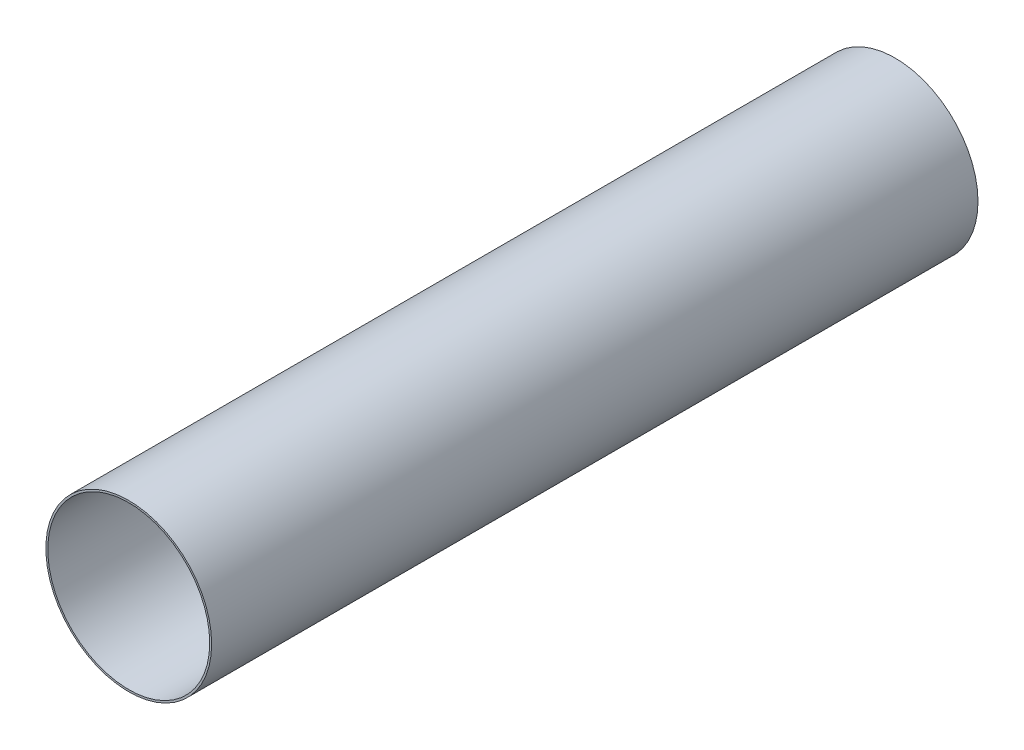
SolidWorks part; units mm, degrees
material "Hexcel AS4C (3000 Filaments)"
ref_plane "Front Plane" through (0, 0, 0) normal (0, 0, 1) x (1, 0, 0)
ref_plane "Top Plane" through (0, 0, 0) normal (0, 1, 0) x (1, 0, 0)
ref_plane "Right Plane" through (0, 0, 0) normal (1, 0, 0) x (0, 0, -1)
sketch "Sketch1" plane through (0, 0, 0) normal (0, 0, 1) x (1, 0, 0)
  circle A0 centre (0, 0) radius 80.518
  circle A1 centre (0, 0) radius 82.4281
  dimension "D1" = 161.036
  dimension "D2" = 164.8562
extrude "Boss-Extrude1" add sketch "Sketch1" along normal blind 762
